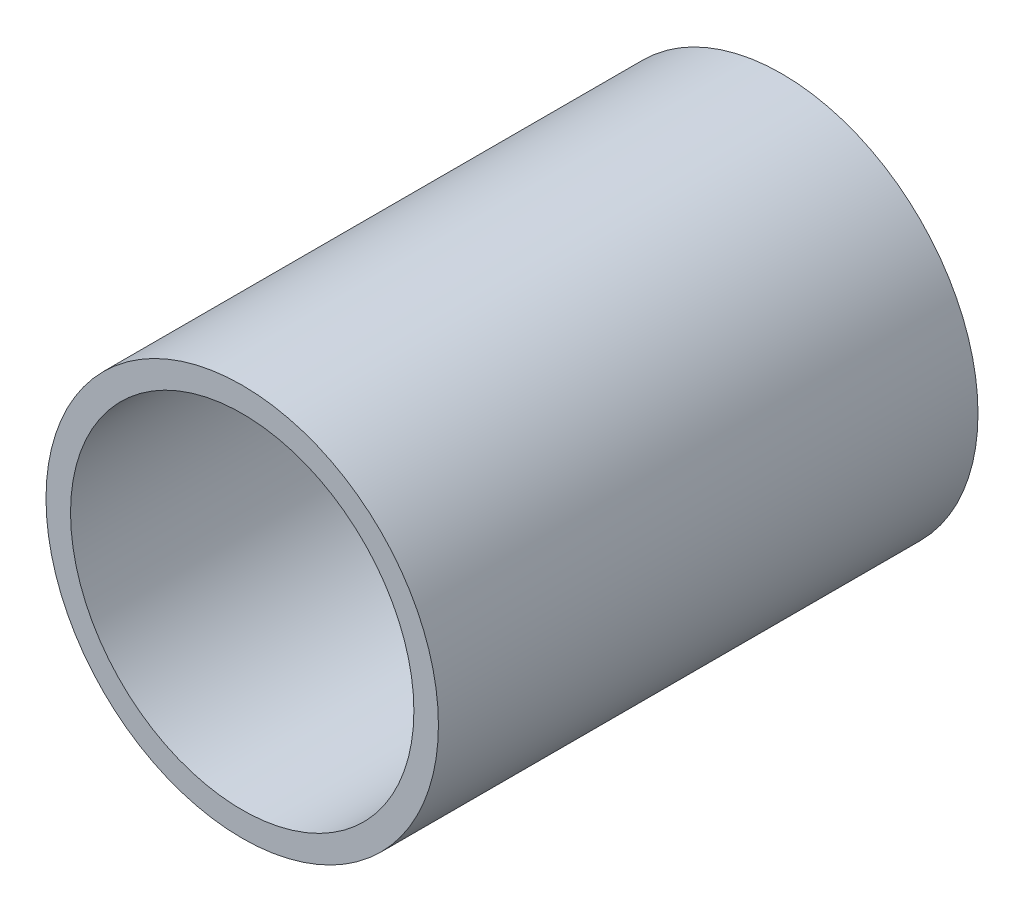
SolidWorks part; units mm, degrees
ref_plane "Front Plane" through (0, 0, 0) normal (0, 0, 1) x (1, 0, 0)
ref_plane "Top Plane" through (0, 0, 0) normal (0, 1, 0) x (1, 0, 0)
ref_plane "Right Plane" through (0, 0, 0) normal (1, 0, 0) x (0, 0, -1)
sketch "Sketch2" plane through (0, 0, 0) normal (0, 0, 1) x (1, 0, 0)
  circle A0 centre (0, 0) radius 40
extrude "Boss-Extrude1" add sketch "Sketch2" along normal blind 110
sketch "Sketch3" plane through (0, 0, 110) normal (0, 0, 1) x (1, 0, 0)
  circle A0 centre (0, 0) radius 35
extrude "Cut-Extrude1" cut sketch "Sketch3" against normal blind 110
